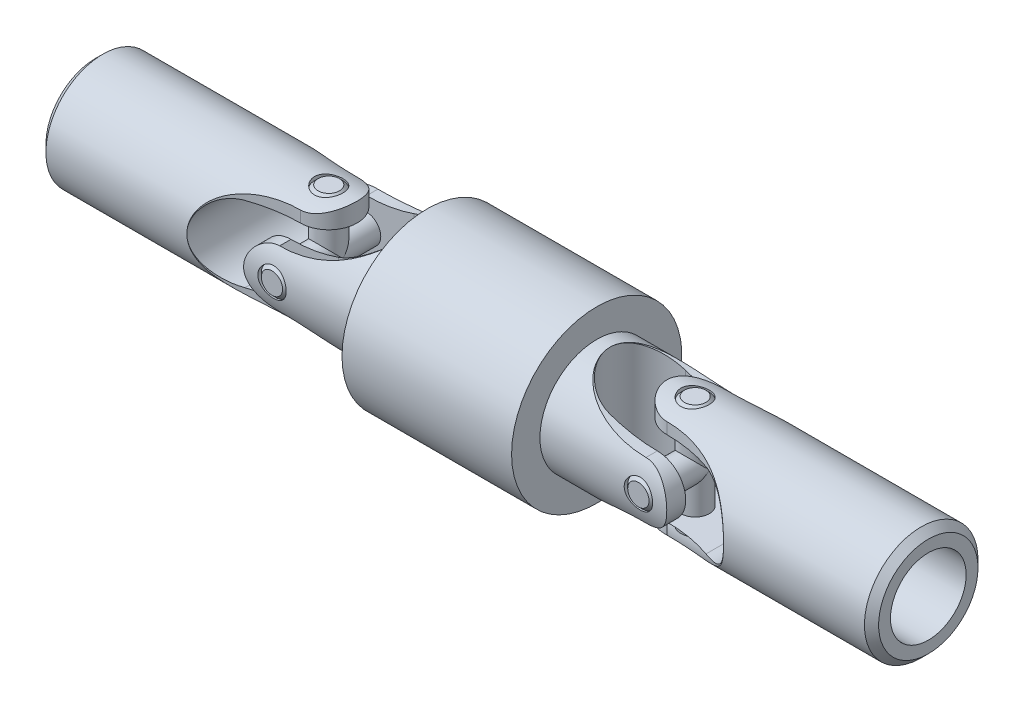
SolidWorks part; units mm, degrees
ref_plane "Front Plane" through (0, 0, 0) normal (0, 0, 1) x (1, 0, 0)
ref_plane "Top Plane" through (0, 0, 0) normal (0, 1, 0) x (1, 0, 0)
ref_plane "Right Plane" through (0, 0, 0) normal (1, 0, 0) x (0, 0, -1)
sketch "Sketch0" plane through (0, 0, 0) normal (0, 1, 0) x (1, 0, 0)
  line L0 (-17.4625, 0) -> (17.4625, 0) construction
  line L1 (-17.4625, 4.7625) -> (-17.4625, -4.7625) construction
  line L2 (-7.9375, 3.175) -> (-7.9375, -3.175) construction
  line L3 (-7.9375, 3.175) -> (-4.7625, 0) construction
  line L4 (-4.7625, 0) -> (-7.9375, -3.175) construction
  line L5 (-6.35, 1.5875) -> (-6.35, -1.5875) construction
  point P7 (-7.9375, 0)
  point P8 (0, 0)
  point P12 (-6.35, 0)
  point P13 (2.0955, 0)
  dimension "D1" = 19.558
ref_plane "Plane2" through (2.0955, 0, 0) normal (1, 0, 0) x (0, 0, -1)
ref_plane "Plane4" through (0, 0, 4.7625) normal (0, 0, 1) x (1, 0, 0)
ref_plane "Plane5" through (17.4625, 0, 0) normal (1, 0, 0) x (0, 0, -1)
sketch "Sketch18" plane through (0, 0, 0) normal (0, 1, 0) x (1, 0, 0)
  line L0 (-17.4625, -3.175) -> (-7.9375, -3.175)
  line L3 (-17.4625, 3.175) -> (-7.9375, 3.175)
  line L4 (-7.9375, 3.175) -> (-7.9375, -3.175)
  line L8 (-7.9375, 3.175) -> (-7.9375, -3.175) construction
  line L12 (17.4625, 0) -> (17.4625, 14.1079) construction
  line L14 (42.8625, 3.175) -> (42.8625, -3.175)
  line L15 (52.3875, 3.175) -> (42.8625, 3.175)
  line L16 (52.3875, -3.175) -> (42.8625, -3.175)
  line L17 (-17.4625, 4.7625) -> (-17.4625, -4.7625) construction
  line L18 (-17.4625, 0) -> (17.4625, 0) construction
sketch "Sketch1" plane through (0, 0, 0) normal (0, 1, 0) x (1, 0, 0)
  line L1 (4.4768, 4.7625) -> (4.4768, 0)
  line L2 (4.4768, 0) -> (-17.4625, 0)
  line L3 (-17.4625, 0) -> (-17.4625, 4.7625)
  line L4 (-17.4625, 4.7625) -> (-17.4625, -4.7625) construction
  line L5 (-17.4625, 0) -> (17.4625, 0) construction
  line L6 (-17.4625, 4.7625) -> (4.4768, 4.7625)
  line L11 (2.0955, 0) -> (6.858, 0) construction
  circle A0 centre (2.0955, 0) radius 4.7625 construction
  dimension "D3" = 21.9393
revolve "Revolve1" add sketch "Sketch1" angle 360 about L0
chamfer "Chamfer1" distance 0.5953 angle 45 1 edges at (-17.4625, 0, 4.7625)
sketch "Sketch2" plane through (0, 0, 0) normal (0, 1, 0) x (1, 0, 0)
  line L0 (-16.8672, 4.7625) -> (-5.0482, 4.7625) construction
  line L1 (-17.4625, 4.7625) -> (4.4768, 4.7625) construction
  line L2 (4.4768, 4.7625) -> (-16.8672, 4.7625) construction
  line L4 (-17.4625, 0) -> (4.4768, 0) construction
  line L5 (-5.0482, 4.7625) -> (6.858, 4.7625)
  line L6 (6.858, 4.7625) -> (6.858, -4.7625)
  line L7 (6.858, -4.7625) -> (-5.0482, -4.7625)
  line L8 (2.0955, 2.3812) -> (2.0955, 0) construction
  line L9 (-17.4625, 0) -> (17.4625, 0) construction
  arc A0 (-5.0482, 4.7625) -> (2.0955, 2.3812) centre (2.0955, 14.2875) ccw
  arc A1 (2.0955, -2.3812) -> (2.0955, 2.3812) centre (2.0955, 0) ccw
  arc A2 (-5.0482, -4.7625) -> (2.0955, -2.3812) centre (2.0955, -14.2875) cw
  dimension "D1" = 4.7625
  dimension "D2" = 7.1437
extrude "Extrude1" cut sketch "Sketch2" against normal through all and the other way through all
sketch "Sketch3" plane through (0, 0, 0) normal (0, 0, 1) x (1, 0, 0)
  line L1 (-1.8764, 3.1718) -> (6.858, 3.1718)
  line L3 (-1.8764, -3.1718) -> (6.858, -3.1718)
  line L4 (6.858, 3.1718) -> (6.858, -3.1718)
  arc A0 (-1.8764, -3.1718) -> (-1.8764, 3.1718) centre (-1.8764, 0) cw
  spline S1 degree 3 poles (2.0955, -4.1244) (1.2914, -4.1244) (0.5029, -4.0811) (-0.6554, -3.9266) (-1.0395, -3.859) (-1.7879, -3.6809) (-2.1487, -3.5713) (-2.8399, -3.2935) (-3.1734, -3.123) (-3.6274, -2.8127) (-3.7714, -2.7001) (-4.0438, -2.4529) (-4.173, -2.3171) (-4.4075, -2.0262) (-4.5131, -1.8713) (-4.6997, -1.5399) (-4.7814, -1.3614) (-4.912, -0.994) (-4.9618, -0.8046) (-5.0298, -0.4137) (-5.0477, -0.2097) (-5.0487, 0.1918) (-5.0325, 0.391) (-4.9662, 0.786) (-4.916, 0.9801) (-4.7868, 1.3485) (-4.7066, 1.5261) (-4.5196, 1.8613) (-4.414, 2.0172) (-4.1803, 2.3089) (-4.0513, 2.4454) (-3.7787, 2.6941) (-3.6348, 2.8071) (-3.1821, 3.1181) (-2.8491, 3.2892) (-2.157, 3.5686) (-1.7973, 3.6781) (-1.0541, 3.8561) (-0.6681, 3.9246) (0.4989, 4.0811) (1.2907, 4.1244) (2.0955, 4.1244) knots 0 0 0 0 0.125 0.125 0.1875 0.1875 0.25 0.25 0.3125 0.3125 0.34375 0.34375 0.375 0.375 0.40625 0.40625 0.4375 0.4375 0.46875 0.46875 0.5 0.5 0.53125 0.53125 0.5625 0.5625 0.59375 0.59375 0.625 0.625 0.65625 0.65625 0.6875 0.6875 0.75 0.75 0.8125 0.8125 0.875 0.875 1 1 1 1 construction
  dimension "D1" = 6.3437
extrude "Extrude3" cut sketch "Sketch3" against normal through all and the other way through all
sketch "Sketch4" plane through (-17.4625, 0, 0) normal (-1, 0, 0) x (0, 0, 1)
  circle A0 centre (0, 0) radius 3.175
extrude "Extrude4" cut sketch "Sketch4" against normal up to vertex (9.525 mm away) up to point (-7.9375, 0, -3.175)
sketch "Sketch6" plane through (0, 0, 0) normal (0, 1, 0) x (1, 0, 0)
  line L0 (-17.4625, 0) -> (17.4625, 0) construction
  line L1 (4.4768, 0) -> (3.2861, 0) construction
  line L2 (3.2861, 0) -> (2.0955, 0) construction
  circle A0 centre (2.0955, 0) radius 1.1906
  arc A1 (2.0955, -2.3812) -> (2.0955, 2.3812) centre (2.0955, 0) ccw construction
  dimension "D1" = 2.3813
extrude "Extrude6" cut sketch "Sketch6" against normal through all and the other way through all
mirror "Mirror1" about plane through (2.0955, 0, 0) normal (1, 0, 0) of bodies 109 122
move or copy body "Body-Move/Copy1" bodies to move or copy 110 copy no rotation origin (0, 0, 0) rotation axis (1, 0, 0) rotation angle 90
sketch "Sketch19" plane through (0, 0, 0) normal (0, 1, 0) x (1, 0, 0)
  line L0 (21.6535, -4.1672) -> (21.6535, 4.1672) construction
  line L1 (17.4625, -4.7625) -> (21.6535, -4.7625)
  line L2 (17.4625, -4.7625) -> (17.4625, 4.7625)
  line L3 (17.4625, 4.7625) -> (21.6535, 4.7625)
  line L4 (21.6535, -4.7625) -> (21.6535, 4.7625)
extrude "Cut-Extrude1" cut sketch "Sketch19" against normal mid plane 76.2
sketch "Sketch14" plane through (0, 0, 0) normal (0, 1, 0) x (1, 0, 0)
  circle A0 centre (2.0955, 0) radius 1.1906 construction
  circle A2 centre (2.0955, 0) radius 1.1906
extrude "Extrude14" add sketch "Sketch14" along normal mid plane 9.525 separate body
sketch "Sketch16" plane through (0, 0, 0) normal (0, 0, 1) x (1, 0, 0)
  circle A0 centre (2.0955, 0) radius 1.1906 construction
  circle A2 centre (2.0955, 0) radius 1.1906
extrude "Extrude16" add sketch "Sketch16" along normal mid plane 9.525
chamfer "Chamfer3" distance 0.2977 angle 45 4 edges at (2.0955, -4.7625, 1.1906) (2.0955, 4.7625, 1.1906) (3.2861, 0, 4.7625) (3.2861, 0, -4.7625)
mirror "Mirror3" about plane through (17.4625, -38.1, 4.7625) normal (-1, 0, 0) of bodies 117 109 151
sketch "Sketch20" plane through (17.4625, 0, 0) normal (1, 0, 0) x (0, 0, -1)
  circle A0 centre (0, 0) radius 7.1438
  circle A1 centre (0, 0) radius 4.7625 construction
  circle A2 centre (0, 0) radius 4.7625
  dimension "D1" = 14.2875
extrude "Boss-Extrude1" add sketch "Sketch20" along normal mid plane 14.224 separate body
move or copy body "Body-Move/Copy2" [suppressed] bodies to move or copy 152 153 154 151 168 copy no rotation origin (2.0955, 0, 0) rotation axis (0, 0, -1) rotation angle 30
move or copy body "Body-Move/Copy3" [suppressed] bodies to move or copy 158 157 copy no rotation origin (28.7119, -15.367, 0) rotation axis (0, 0, 1) rotation angle 30
equation "\"D2@Sketch3\" = \"D1@Sketch3\" / 4"
equation "\"D1@Extrude14\" = \"OD@Sketch0\""
equation "\"D1@Extrude16\" = \"D1@Extrude14\""
equation "\"D1@Sketch3\" = \"OD@Sketch0\"*.666"
equation "\"D1@Chamfer1\" = \"OD@Sketch0\"/16"
equation "\"D1@Chamfer3\" = \"D1@Chamfer1\"*.50"
equation "\"D2@Sketch2\" = \"D1@Sketch2\"*1.5"
equation "\"D1@Sketch0\" = \"OAL@Sketch0\"*.56"
